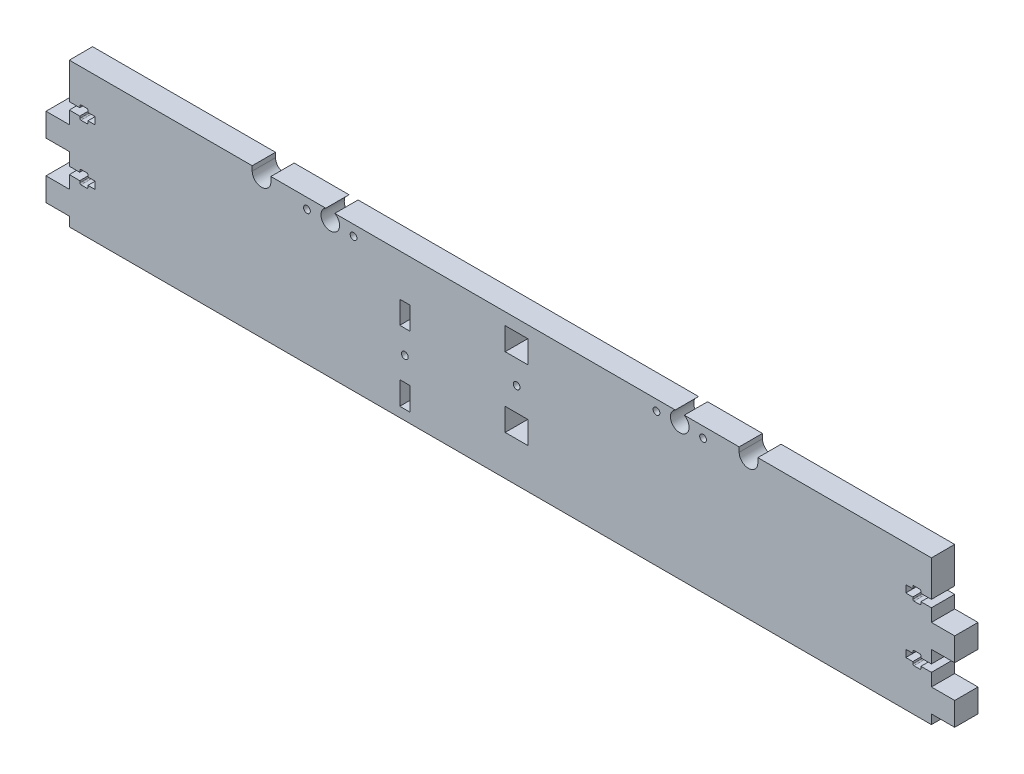
SolidWorks part; units mm, degrees
ref_plane "Front Plane" through (0, 0, 0) normal (0, 0, 1) x (1, 0, 0)
ref_plane "Top Plane" through (0, 0, 0) normal (0, 1, 0) x (1, 0, 0)
ref_plane "Right Plane" through (0, 0, 0) normal (1, 0, 0) x (0, 0, -1)
sketch "Sketch1" plane through (0, 0, 0) normal (0, 0, 1) x (1, 0, 0)
  line L0 (0, 0) -> (-185, 0)
  line L1 (-185, 0) -> (-185, -62) construction
  line L2 (0, -62) -> (-185, -62)
  line L3 (-185, -62) -> (-185, -58)
  line L4 (-185, -58) -> (-195, -58)
  line L5 (-195, -58) -> (-195, -48)
  line L6 (-195, -48) -> (-185, -48)
  line L7 (-185, -48) -> (-185, -34)
  line L8 (-185, -34) -> (-195, -34)
  line L9 (-195, -34) -> (-195, -24)
  line L10 (-195, -24) -> (-185, -24)
  line L11 (0, -62) -> (0, 0)
  line L12 (-185, -24) -> (-185, 0)
  line L13 (-195, -58) -> (-195, -24) construction
  line L14 (-195, -29) -> (-185, -29) construction
  line L15 (-195, -53) -> (-185, -53) construction
  dimension "D1" = 185
  dimension "D2" = 10
  dimension "D3" = 10
  dimension "D4" = 10
  dimension "D5" = 24
  dimension "D6" = 29
  dimension "D7" = 62
extrude "MainBody" add sketch "Sketch1" along normal blind 10
sketch "Sketch3" plane through (0, 0, 10) normal (0, 0, 1) x (1, 0, 0)
  line L0 (-185, -17) -> (-174, -17) construction
  line L1 (-185, 0) -> (-185, -24) construction
  line L2 (-185, -18.55) -> (-180.5, -18.55)
  line L3 (-180.5, -18.55) -> (-180.5, -19.35)
  line L4 (-180, -19.85) -> (-177.5, -19.85)
  line L5 (-177, -19.35) -> (-177, -18.55)
  line L6 (-177, -18.55) -> (-174, -18.55)
  line L7 (-174, -18.55) -> (-174, -15.45)
  line L8 (-180.5, -18.55) -> (-177, -18.55) construction
  line L9 (-195, -24) -> (-195, -34) construction
  line L10 (-180.5, -15.45) -> (-177, -15.45) construction
  line L11 (-177, -15.45) -> (-174, -15.45)
  line L12 (-177, -14.65) -> (-177, -15.45)
  line L13 (-180, -14.15) -> (-177.5, -14.15)
  line L14 (-180.5, -15.45) -> (-180.5, -14.65)
  line L15 (-185, -15.45) -> (-180.5, -15.45)
  line L16 (-185, -18.55) -> (-185, -15.45)
  line L17 (-185, -24) -> (-185, -34) construction
  line L19 (-195, -24) -> (-195, -34) construction
  line L20 (-195, -29) -> (-185, -29) construction
  line L21 (-180.5, -42.55) -> (-177, -42.55) construction
  line L22 (-180.5, -39.45) -> (-177, -39.45) construction
  line L23 (-185, -41) -> (-174, -41) construction
  line L24 (-185, -39.45) -> (-185, -42.55)
  line L25 (-185, -42.55) -> (-180.5, -42.55)
  line L26 (-180.5, -42.55) -> (-180.5, -43.35)
  line L27 (-180, -43.85) -> (-177.5, -43.85)
  line L28 (-177, -43.35) -> (-177, -42.55)
  line L29 (-177, -42.55) -> (-174, -42.55)
  line L30 (-174, -39.45) -> (-174, -42.55)
  line L31 (-177, -39.45) -> (-174, -39.45)
  line L32 (-177, -38.65) -> (-177, -39.45)
  line L33 (-180, -38.15) -> (-177.5, -38.15)
  line L34 (-180.5, -39.45) -> (-180.5, -38.65)
  line L35 (-185, -39.45) -> (-180.5, -39.45)
  line L36 (-180.5, -15.45) -> (-177, -15.45) construction
  arc A0 (-177.5, -19.85) -> (-177, -19.35) centre (-177.5, -19.35) ccw
  arc A1 (-180.5, -19.35) -> (-180, -19.85) centre (-180, -19.35) ccw
  arc A2 (-180.5, -14.65) -> (-180, -14.15) centre (-180, -14.65) cw
  arc A3 (-177.5, -14.15) -> (-177, -14.65) centre (-177.5, -14.65) cw
  arc A4 (-177.5, -43.85) -> (-177, -43.35) centre (-177.5, -43.35) ccw
  arc A5 (-180.5, -43.35) -> (-180, -43.85) centre (-180, -43.35) ccw
  arc A6 (-180.5, -38.65) -> (-180, -38.15) centre (-180, -38.65) cw
  arc A7 (-177.5, -38.15) -> (-177, -38.65) centre (-177.5, -38.65) cw
  point P6 (-195, -29)
  point P15 (-177, -19.85)
  point P18 (-180.5, -19.85)
  point P29 (-180.5, -14.15)
  point P30 (-177, -14.15)
  point P62 (-177, -43.85)
  point P63 (-180.5, -43.85)
  point P64 (-180.5, -38.15)
  point P65 (-177, -38.15)
  dimension "D2" = 8
  dimension "D7" = 0.5
  dimension "D1" = 11
  dimension "D3" = 1.55
  dimension "D4" = 2.85
  dimension "D5" = 12
  dimension "D6" = 3.5
extrude "ScrewCutouts" cut sketch "Sketch3" against normal through all
mirror "Mirror1" about plane through (0, 0, 0) normal (1, 0, 0) of "ScrewCutouts", "MainBody"
sketch "Sketch2" plane through (0, 0, 10) normal (0, 0, 1) x (1, 0, 0)
  line L0 (0, 0) -> (0, -62) construction
  line L1 (-185, -62) -> (185, -62) construction
  line L2 (2, 0) -> (2, -62) construction
  line L3 (185, 0) -> (-185, 0) construction
  line L4 (-63, -4.5) -> (-83, -4.5) construction
  line L5 (-73, -7.5) -> (-73, 0.5) construction
  line L6 (77, -7.5) -> (77, 0.5) construction
  line L7 (67, -4.5) -> (87, -4.5) construction
  circle A0 centre (-73, -3.5) radius 4
  circle A1 centre (-83, -4.5) radius 1.45
  circle A2 centre (-63, -4.5) radius 1.45
  circle A3 centre (67, -4.5) radius 1.45
  circle A4 centre (87, -4.5) radius 1.45
  circle A5 centre (77, -3.5) radius 4
  dimension "D1" = 2.9
  dimension "D2" = 8
  dimension "D4" = 3.5
  dimension "D5" = 75
  dimension "D6" = 2
  dimension "D3" = 10
  dimension "D7" = 1
extrude "RodCutouts" cut sketch "Sketch2" against normal through all
sketch "Sketch4" plane through (0, 0, 10) normal (0, 0, 1) x (1, 0, 0)
  line L0 (77, -3.5) -> (-73, -3.5) construction
  line L1 (2, -3.5) -> (2, -62) construction
  line L2 (-185, -62) -> (185, -62) construction
  line L3 (7, -44.85) -> (7, -5.15) construction
  line L4 (75.0635, 0) -> (-71.0635, 0) construction
  line L5 (7, -10) -> (7, -40) construction
  line L6 (2.075, -5.15) -> (11.925, -5.15)
  line L7 (2.075, -5.15) -> (2.075, -14.85)
  line L8 (2.075, -14.85) -> (11.925, -14.85)
  line L9 (11.925, -5.15) -> (11.925, -14.85)
  line L10 (2.075, -5.15) -> (11.925, -14.85) construction
  line L11 (2.075, -14.85) -> (11.925, -5.15) construction
  line L12 (2.075, -35.15) -> (11.925, -35.15)
  line L13 (2.075, -35.15) -> (2.075, -44.85)
  line L14 (2.075, -44.85) -> (11.925, -44.85)
  line L15 (11.925, -35.15) -> (11.925, -44.85)
  line L16 (2.075, -35.15) -> (11.925, -44.85) construction
  line L17 (2.075, -44.85) -> (11.925, -35.15) construction
  circle A0 centre (7, -25) radius 1.45
  point P12 (7, -10)
  point P17 (7, -40)
  dimension "D8" = 2.9
  dimension "D1" = 9.85
  dimension "D2" = 9.7
  dimension "D3" = 9.85
  dimension "D4" = 9.7
  dimension "D5" = 30
  dimension "D6" = 10
  dimension "D7" = 5
extrude "Cut-Extrude3" cut sketch "Sketch4" against normal through all
sketch "Sketch5" plane through (0, 0, 10) normal (0, 0, 1) x (1, 0, 0)
  line L0 (-41, 0) -> (-41, -62) construction
  line L1 (-74.9365, 0) -> (-185, 0) construction
  line L2 (-185, -62) -> (185, -62) construction
  line L3 (-43.175, -27.65) -> (-43.175, -47.85) construction
  line L4 (-43.175, -17.95) -> (-38.825, -17.95)
  line L5 (-43.175, -17.95) -> (-43.175, -27.65)
  line L6 (-43.175, -27.65) -> (-38.825, -27.65)
  line L7 (-38.825, -17.95) -> (-38.825, -27.65)
  line L8 (-43.175, -17.95) -> (-38.825, -27.65) construction
  line L9 (-43.175, -27.65) -> (-38.825, -17.95) construction
  line L10 (-43.175, -47.85) -> (-38.825, -47.85)
  line L11 (-43.175, -47.85) -> (-43.175, -57.75)
  line L12 (-43.175, -57.75) -> (-38.825, -57.75)
  line L13 (-38.825, -47.85) -> (-38.825, -57.75)
  line L14 (-43.175, -47.85) -> (-38.825, -57.75) construction
  line L15 (-43.175, -57.75) -> (-38.825, -47.85) construction
  line L16 (-38.825, -47.85) -> (-38.825, -27.65) construction
  line L17 (-43.175, -37.75) -> (-38.825, -37.75) construction
  line L18 (-73, -3.5) -> (77, -3.5) construction
  line L19 (2, -3.5) -> (2, -62) construction
  line L20 (2, -32.75) -> (-195, -32.75) construction
  line L21 (-195, -24) -> (-195, -34) construction
  line L22 (-34.625, 8.9944) -> (-34.625, 5) construction
  line L23 (75.0635, 0) -> (-71.0635, 0) construction
  line L24 (-31.425, 8.9944) -> (-31.425, 5)
  line L25 (-37.825, 8.9944) -> (-37.825, 5)
  circle A0 centre (-41, -37.75) radius 1.45
  arc A1 (-31.425, 8.9944) -> (-37.825, 8.9944) centre (-34.625, 8.9944) ccw
  arc A2 (-37.825, 5) -> (-31.425, 5) centre (-34.625, 5) ccw
  point P6 (-41, -22.8)
  point P11 (-41, -52.8)
  point P34 (-34.625, 6.9972)
  dimension "D4" = 9.7
  dimension "D5" = 30
  dimension "D6" = 2.9
  dimension "D9" = 3.2
  dimension "D1" = 4.35
  dimension "D2" = 0
  dimension "D3" = 9.9
  dimension "D7" = 43
  dimension "D8" = 5
  dimension "D10" = 5
  dimension "D11" = 1
extrude "EndstopHolder" cut sketch "Sketch5" against normal through all
sketch "Sketch6" plane through (0, 0, 10) normal (0, 0, 1) x (1, 0, 0)
  line L0 (-43.175, -47.85) -> (-43.175, -27.65) construction
  line L1 (-42.35, -47.85) -> (-30.825, -47.85) construction
  line L3 (-30.825, -53.85) -> (-30.825, -41.85) construction
  line L4 (-32.825, -53.85) -> (-32.825, -41.85)
  line L5 (-28.825, -53.85) -> (-28.825, -41.85)
  line L6 (-38.825, -47.85) -> (-43.175, -47.85) construction
  line L7 (-38.825, -57.75) -> (-38.825, -47.85) construction
  arc A0 (-32.825, -53.85) -> (-28.825, -53.85) centre (-30.825, -53.85) ccw
  arc A1 (-28.825, -41.85) -> (-32.825, -41.85) centre (-30.825, -41.85) ccw
  point P10 (-30.825, -47.85)
  dimension "D1" = 2
  dimension "D2" = 12
  dimension "D3" = 8
  dimension "D4" = 0
extrude "EndstopWires" [suppressed] cut sketch "Sketch6" against normal through all
sketch "Sketch7" plane through (0, 0, 10) normal (0, 0, 1) x (1, 0, 0)
  line L0 (-73, -3.5) -> (77, -3.5) construction
  line L1 (2, -3.5) -> (2, -62) construction
  line L3 (-102.5, 0) -> (-102.5, -2) construction
  line L4 (-74.9365, 0) -> (-185, 0) construction
  line L5 (-98.5, 0) -> (-98.5, -2)
  line L6 (-106.5, 0) -> (-106.5, -2)
  line L7 (106.5, 0) -> (106.5, -2) construction
  line L8 (102.5, 0) -> (102.5, -2)
  line L9 (110.5, 0) -> (110.5, -2)
  line L10 (-185, -62) -> (185, -62) construction
  arc A0 (-98.5, 0) -> (-106.5, 0) centre (-102.5, 0) ccw
  arc A1 (-106.5, -2) -> (-98.5, -2) centre (-102.5, -2) ccw
  arc A2 (102.5, 0) -> (110.5, 0) centre (106.5, 0) cw
  arc A3 (110.5, -2) -> (102.5, -2) centre (106.5, -2) cw
  point P12 (-102.5, -1)
  point P19 (106.5, -1)
  dimension "D3" = 4
  dimension "D1" = 2
  dimension "D2" = 104.5
extrude "Cut-Extrude4" cut sketch "Sketch7" against normal through all
equation "\"Y-ROD-SPACING\"=75"
equation "\"D5@Sketch2\"=\"Y-ROD-SPACING\""
equation "\"Y-BED-OFFSET\"=2"
equation "\"D6@Sketch2\"=\"Y-BED-OFFSET\""
equation "\"T-SLOT-NUT-FILLET-RADIUS\"=0.5"
equation "\"D7@Sketch3\"=\"T-SLOT-NUT-FILLET-RADIUS\""
equation "\"T-SLOT-SCREW-SHAFT-RADIUS\"=1.55"
equation "\"D3@Sketch3\"=\"T-SLOT-SCREW-SHAFT-RADIUS\""
equation "\"T-SLOT-SCREW-SHAFT-CUTOUT-LENGTH\"=11"
equation "\"D1@Sketch3\"=\"T-SLOT-SCREW-SHAFT-CUTOUT-LENGTH\""
equation "\"T-SLOT-NUT-DEPTH\"=3.5"
equation "\"D6@Sketch3\"=\"T-SLOT-NUT-DEPTH\""
equation "\"T-SLOT-NUT-WIDTH\"=2.85"
equation "\"D4@Sketch3\"=\"T-SLOT-NUT-WIDTH\""
equation "\"T-SLOT-NUT-END-DISTANCE\"=8"
equation "\"D2@Sketch3\"=\"T-SLOT-NUT-END-DISTANCE\""
equation "\"ACRYLIC-TAB-CUTOUT-SIZE\"=\"ACRYLIC-THICKNESS\"+\"ACRYLIC-TAB-TOLERANCE\"*2"
equation "\"D1@Sketch4\"=\"ACRYLIC-THICKNESS\"-\"KERF\"*2"
equation "\"D2@Sketch4\"=\"ACRYLIC-TAB-WIDTH\"-\"KERF\"*4"
equation "\"D3@Sketch4\"=\"ACRYLIC-THICKNESS\"-\"KERF\"*2"
equation "\"D4@Sketch4\"=\"ACRYLIC-TAB-WIDTH\"-\"KERF\"*4"
equation "\"ACRYLIC-M3-HOLE\"=2.9"
equation "\"D8@Sketch4\"=\"ACRYLIC-M3-HOLE\""
equation "\"Y-BED-ROD-INSET\"=3.5"
equation "\"D1@Sketch2\"=\"ACRYLIC-M3-HOLE\""
equation "\"D4@Sketch2\"=\"Y-BED-ROD-INSET\""
equation "\"SMOOTHROD-CAP-SCREW-DISTANCE\"=20"
equation "\"D3@Sketch2\"=\"SMOOTHROD-CAP-SCREW-DISTANCE\"/2"
equation "\"ACRYLIC-TAB-WIDTH\"=\"ACRYLIC-THICKNESS\""
equation "\"FRAME-WIDTH-INNER\"=370"
equation "\"D2@Sketch1\"=\"ACRYLIC-TAB-WIDTH\""
equation "\"D3@Sketch1\"=\"ACRYLIC-TAB-WIDTH\""
equation "\"D4@Sketch1\"=\"ACRYLIC-TAB-WIDTH\""
equation "\"D1@Sketch1\"=\"FRAME-WIDTH-INNER\"/2"
equation "\"X-ROD-SPACING\"=45"
equation "\"Z-ROD-SPACING\"=17.5"
equation "\"ACRYLIC-THICKNESS\"=10"
equation "\"ACRYLIC-THICKNESS2\"=4.5"
equation "\"NEMA17-HOLE-SPACING\"=31"
equation "\"NEMA17-CENTRAL-CUTOUT\"=22.5"
equation "\"Z-BRACKET-REACH\"=57"
equation "\"TOP-BRACKET-SPACING\"=40"
equation "\"SMOOTHROD-X-LENGTH\"=350"
equation "\"SMOOTHROD-Y-LENGTH\"=350"
equation "\"SMOOTHROD-Z-LENGTH\"=350"
equation "\"SMOOTHROD-TIGHTENING-HEADROOM\"=.25"
equation "\"LEADSCREW-Z-LENGTH\"=300"
equation "\"SCREW-LENGTH-FRAME\"=\"ACRYLIC-THICKNESS\" + 10"
equation "\"SCREW-HEAD-RADIUS\"=6"
equation "\"PRINTED-X-SMOOTHROD-DIAMETER\"=8.8"
equation "\"PRINTED-X-SMOOTHROD-CUTOUT\"=10"
equation "\"PRINTED-X-BASE-HEIGHT\"=10"
equation "\"PRINTED-LM8UU-CUTOUT-SIZE\"=15.5"
equation "\"PRINTED-LM8UU-CUTOUT-LENGTH\"=24.5"
equation "\"PRINTED-X-IDLER-HEIGHT\"=16"
equation "\"PSU-MOUNTING-WIDTH\"=95"
equation "\"PSU-MOUNTING-HEIGHT\"=177"
equation "\"D1@MainBody\"=\"ACRYLIC-THICKNESS\""
equation "\"D1@Sketch5\"=\"ACRYLIC-THICKNESS2\"-\"KERF\"*2"
equation "\"D3@Sketch5\"=\"ACRYLIC-TAB-CUTOUT-SIZE\""
equation "\"D4@Sketch5\"=\"ACRYLIC-TAB-WIDTH\"-\"KERF\"*4"
equation "\"D6@Sketch5\"=\"ACRYLIC-M3-HOLE\""
equation "\"Y-BED-SCREW-SPACING\"=209"
equation "\"Y-BED-SCREW-CUTOUT-SLOT-HEIGHT\"=2"
equation "\"Z-ROD-INSET\"=13.5"
equation "\"Y-BELT-TO-ROD-DISTANCE\"=20"
equation "\"SPOOL-HOLDER-ROD-SPACING\"=150"
equation "\"D1@Sketch7\"=\"Y-BED-SCREW-CUTOUT-SLOT-HEIGHT\""
equation "\"D2@Sketch7\"=\"Y-BED-SCREW-SPACING\"/2"
equation "\"ACRYLIC-TAB-TOLERANCE\"=-.05"
equation "\"SCREW-LENGTH-MOTOR\"=\"ACRYLIC-THICKNESS\" + 5"
equation "\"SCREW-LENGTH-EXTRUDER\"=28"
equation "\"ACRYLIC-X-CARRIAGE-WIDTH\"=55"
equation "\"ACRYLIC-X-CARRIAGE-HEIGHT\"=75"
equation "\"ACRYLIC-X-CARRIAGE-LM8UU-CUTOUT-WIDTH\"=24.25"
equation "\"ACRYLIC-X-CARRIAGE-SCREW-SPACING-X\"=15"
equation "\"ACRYLIC-X-CARRIAGE-SCREW-SPACING-Y\"=33"
equation "\"ACRYLIC-X-CARRIAGE-CENTER-TAB-SPACING\"=14"
equation "\"ACRYLIC-X-CARRIAGE-EXTRUDER-OFFSET\"=26"
equation "\"ACRYLIC-X-CARRIAGE-EXTRUDER-ANGLE\"=90"
equation "\"ACRYLIC-X-CARRIAGE-EXTRUDER-SHELF-DEPTH\"=\"ACRYLIC-X-CARRIAGE-EXTRUDER-OFFSET\" + 28"
equation "\"ACRYLIC-X-CARRIAGE-EXTRUDER-BRACE-SPACING\"=23"
equation "\"ACRYLIC-X-CARRIAGE-EXTRUDER-BRACE-TAB-OFFSET\"=20"
equation "\"ACRYLIC-X-CARRIAGE-EXTRUDER-BRACE-HEIGHT\"=35"
equation "\"ACRYLIC-X-CARRIAGE-EXTRUDER-BRACE-SCREW-SPACING\"=22"
equation "\"PRINTED-M3-HOLE\"=3.5"
equation "\"ACRYLIC-X-CARRIAGE-LM8UU-CUTOUT-HEIGHT\"=11.0"
equation "\"ACRYLIC-X-CARRIAGE-DUAL-WIDTH-MULTIPLIER\"=1.65"
equation "\"ACRYLIC-X-CARRIAGE-DUAL-HOTEND-SPACING\"=42"
equation "\"ACRYLIC-X-CARRIAGE-DUAL-WIDTH\"=75"
equation "\"ACRYLIC-X-CARRIAGE-DUAL-HOTEND-SEPARATION\"=36"
equation "\"ACRYLIC-X-CARRIAGE-DUAL-MOUNT-PLATE-DEPTH\"=75"
equation "\"ACRYLIC-X-CARRIAGE-DUAL-MOUNT-BRACE-WIDTH\"=33"
equation "\"ACRYLIC-X-CARRIAGE-DUAL-MOUNT-SCREW-WIDTH\"=40"
equation "\"BLOWER-FAN-WIDTH\"=15"
equation "\"KERF\"=0.075"
equation "\"PRINTED-M3-NUT-AF\"=6.25"
equation "\"ACRYLIC-X-CARRIAGE-DUAL-FAN-OFFSET\"=52"
equation "\"ACRYLIC-X-CARRIAGE-DUAL-FAN-HEIGHT\"=20"
